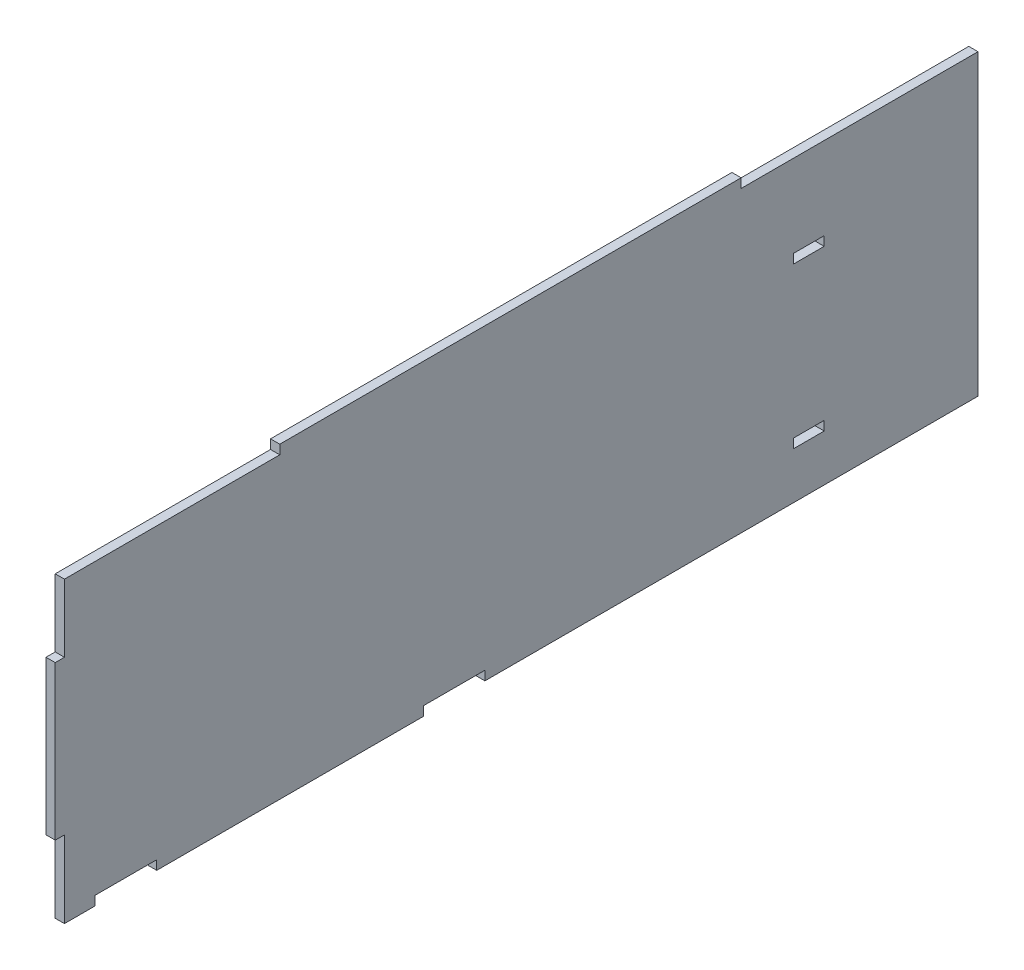
SolidWorks part; units mm, degrees
ref_plane "Plan de face" through (0, 0, 0) normal (0, 0, 1) x (1, 0, 0)
ref_plane "Plan de dessus" through (0, 0, 0) normal (0, 1, 0) x (1, 0, 0)
ref_plane "Plan de droite" through (0, 0, 0) normal (1, 0, 0) x (0, 0, -1)
ref_plane "Plan1" through (3, 0, 0) normal (1, 0, 0) x (0, 0, -1)
sketch "Esquisse1" plane through (3, 0, 0) normal (1, 0, 0) x (0, 0, -1)
  line L0 (123.2981, -36.4365) -> (123.2981, -39.4365)
  line L1 (123.2981, -39.4365) -> (113.2981, -39.4365)
  line L2 (113.2981, -39.4365) -> (113.2981, -36.4365)
  line L3 (113.2981, -36.4365) -> (123.2981, -36.4365)
  line L4 (-123.7019, -54.6365) -> (-113.7019, -54.6365)
  line L5 (-113.7019, -54.6365) -> (-113.7019, -51.6365)
  line L6 (-113.7019, -51.6365) -> (-93.7019, -51.6365)
  line L7 (-93.7019, -51.6365) -> (-93.7019, -54.6365)
  line L8 (-93.7019, -54.6365) -> (-7.0019, -54.6365)
  line L9 (-7.0019, -54.6365) -> (-7.0019, -51.6365)
  line L10 (-7.0019, -51.6365) -> (12.9981, -51.6365)
  line L11 (12.9981, -51.6365) -> (12.9981, -54.6365)
  line L12 (12.9981, -54.6365) -> (173.2981, -54.6365)
  line L13 (173.2981, -54.6365) -> (173.2981, 42.3635)
  line L14 (173.2981, 42.3635) -> (96.2981, 42.3635)
  line L15 (96.2981, 42.3635) -> (96.2981, 45.3635)
  line L16 (96.2981, 45.3635) -> (-53.7019, 45.3635)
  line L17 (-53.7019, 45.3635) -> (-53.7019, 42.3635)
  line L18 (-53.7019, 42.3635) -> (-123.7019, 42.3635)
  line L19 (-123.7019, 42.3635) -> (-123.7019, 20.3635)
  line L20 (-123.7019, 20.3635) -> (-126.7019, 20.3635)
  line L21 (-126.7019, 20.3635) -> (-126.7019, -29.6365)
  line L22 (-126.7019, -29.6365) -> (-123.7019, -29.6365)
  line L23 (-123.7019, -29.6365) -> (-123.7019, -54.6365)
  line L24 (113.2981, 12.5635) -> (113.2981, 15.5635)
  line L25 (113.2981, 15.5635) -> (123.2981, 15.5635)
  line L26 (123.2981, 15.5635) -> (123.2981, 12.5635)
  line L27 (123.2981, 12.5635) -> (113.2981, 12.5635)
  dimension "D1" = 26.8
  dimension "D2" = 97
  dimension "D3" = 15.2
  dimension "D4" = 50
  dimension "D5" = 50
  dimension "D6" = 3
  dimension "D7" = 3
  dimension "D8" = 49
extrude "Boss.-Extru.1" add sketch "Esquisse1" against normal blind 3
